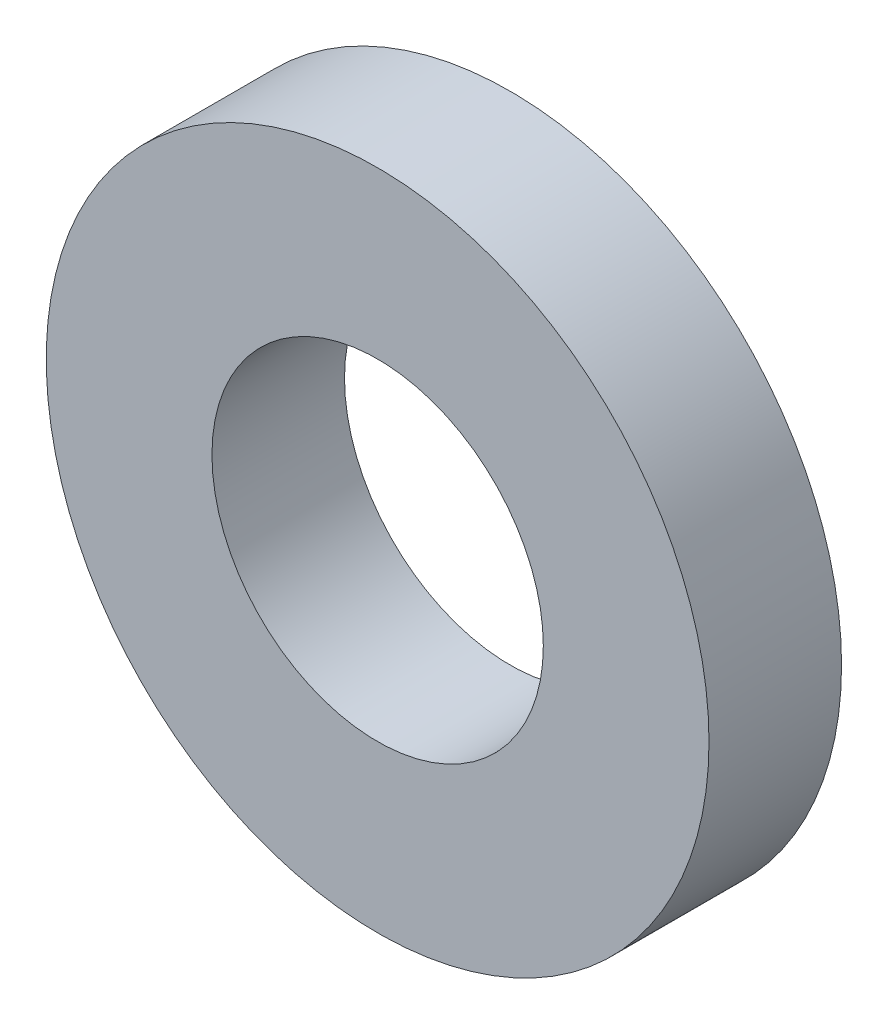
SolidWorks part; units mm, degrees
ref_plane "Front Plane" through (0, 0, 0) normal (0, 0, 1) x (1, 0, 0)
ref_plane "Top Plane" through (0, 0, 0) normal (0, 1, 0) x (1, 0, 0)
ref_plane "Right Plane" through (0, 0, 0) normal (1, 0, 0) x (0, 0, -1)
sketch "Sketch1" plane through (0, 0, 0) normal (0, 0, 1) x (1, 0, 0)
  circle A0 centre (0, 0) radius 10
  circle A1 centre (0, 0) radius 5
  dimension "D1" = 20
  dimension "D2" = 10
extrude "Boss-Extrude1" add sketch "Sketch1" along normal blind 4
